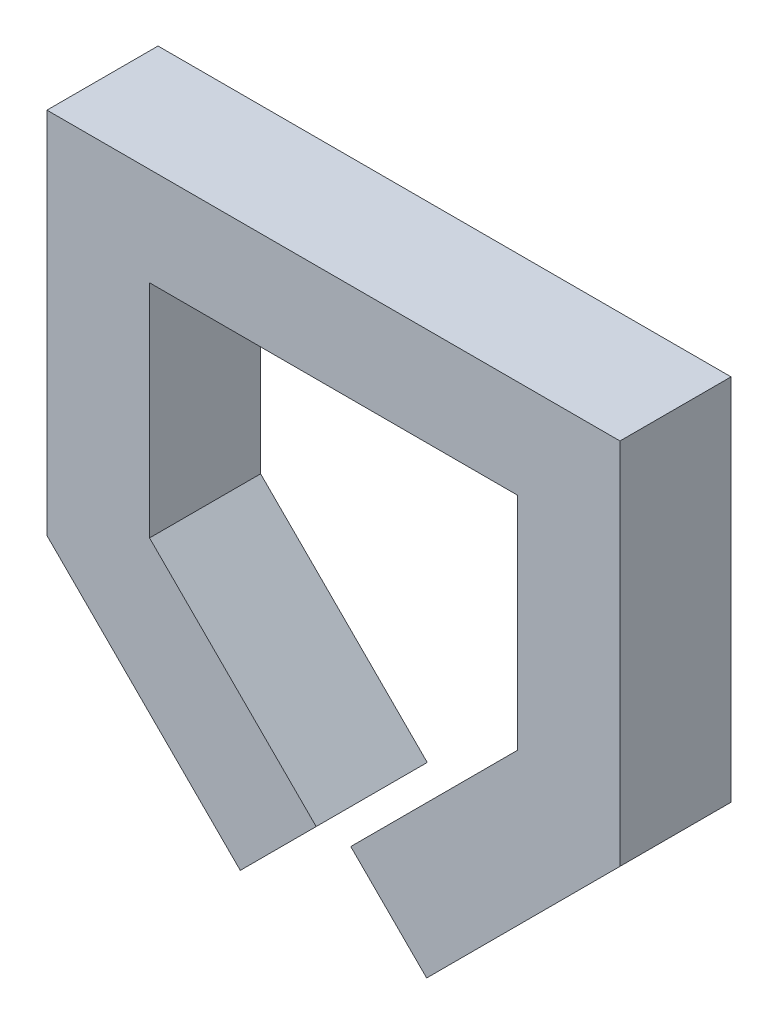
SolidWorks part; units mm, degrees
ref_plane "Front Plane" through (0, 0, 0) normal (0, 0, 1) x (1, 0, 0)
ref_plane "Top Plane" through (0, 0, 0) normal (0, 1, 0) x (1, 0, 0)
ref_plane "Right Plane" through (0, 0, 0) normal (1, 0, 0) x (0, 0, -1)
sketch "Sketch2" plane through (0, 0, 0) normal (0, 0, 1) x (1, 0, 0)
  line L35 (121.2621, -54.9453) -> (86.4478, -20.131)
  line L36 (86.4478, -20.131) -> (86.4478, 46.2157)
  line L37 (86.4478, 46.2157) -> (189.6393, 46.2157)
  line L38 (121.2621, -54.9453) -> (134.9302, -41.2773)
  line L39 (134.9302, -41.2773) -> (104.921, -11.2681)
  line L40 (104.921, -11.2681) -> (104.921, 28.5299)
  line L41 (104.921, 28.5299) -> (171.1661, 28.5299)
  line L43 (171.1661, -11.2681) -> (171.1661, 28.5299)
  line L44 (141.157, -41.2773) -> (171.1661, -11.2681)
  line L45 (154.825, -54.9453) -> (141.157, -41.2773)
  line L46 (189.6393, -20.131) -> (189.6393, 46.2157)
  line L47 (154.825, -54.9453) -> (189.6393, -20.131)
  point P44 (138.0436, 28.5299)
extrude "Boss-Extrude1" add sketch "Sketch2" along normal blind 20 contours L37 L46 L47 L45 L44 L43 L41 L40 L39 L38 L35 L36
